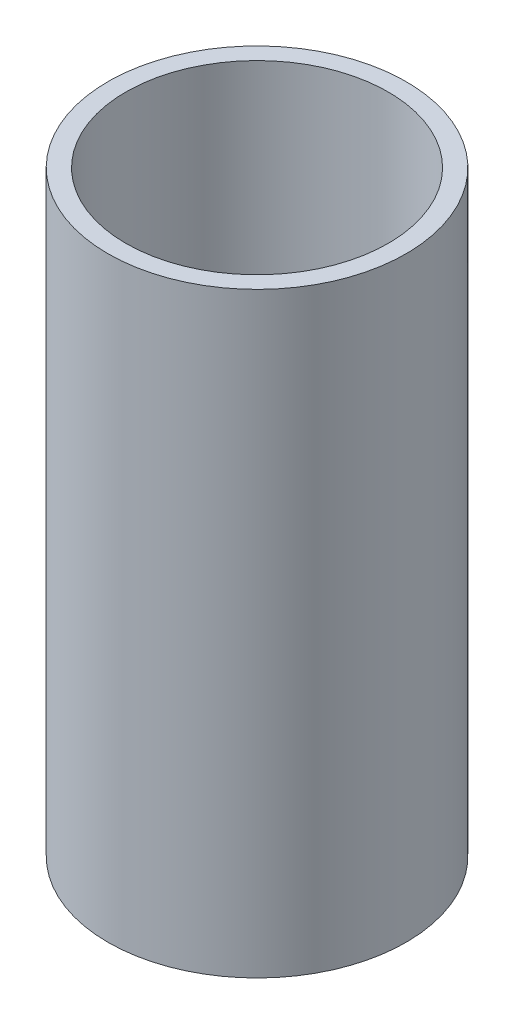
SolidWorks part; units mm, degrees
ref_plane "前基準面" through (0, 0, 0) normal (0, 0, 1) x (1, 0, 0)
ref_plane "上基準面" through (0, 0, 0) normal (0, 1, 0) x (1, 0, 0)
ref_plane "右基準面" through (0, 0, 0) normal (1, 0, 0) x (0, 0, -1)
sketch "草圖1" plane through (0, 0, 0) normal (0, 1, 0) x (1, 0, 0)
  circle A0 centre (0, 0) radius 25
  circle A1 centre (0, 0) radius 22
  dimension "D1" = 50
  dimension "D2" = 44
extrude "填料-伸長1" add sketch "草圖1" along normal blind 100
